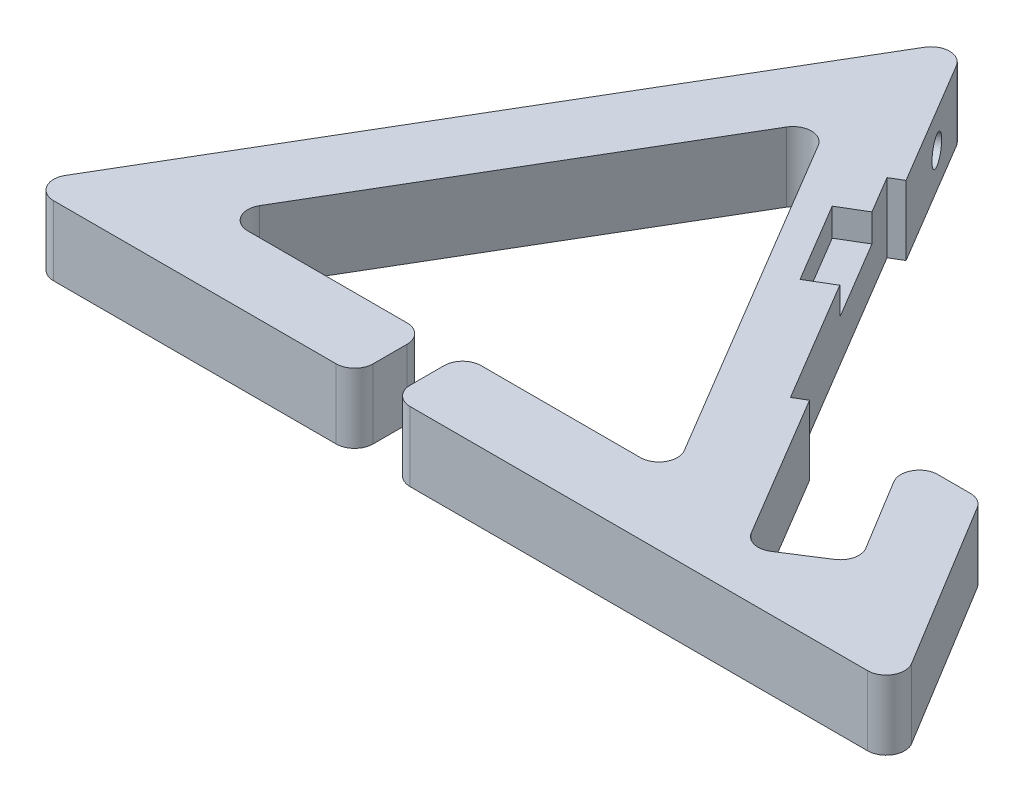
SolidWorks part; units mm, degrees
ref_plane "Front Plane" through (0, 0, 0) normal (0, 0, 1) x (1, 0, 0)
ref_plane "Top Plane" through (0, 0, 0) normal (0, 1, 0) x (1, 0, 0)
ref_plane "Right Plane" through (0, 0, 0) normal (1, 0, 0) x (0, 0, -1)
sketch "Sketch1" plane through (0, 0, 0) normal (0, 1, 0) x (1, 0, 0)
  line L0 (-46.2925, 32.1196) -> (-39.6941, 28.2314) construction
  line L1 (-13.4081, 32.1196) -> (-20.2717, 28.7214) construction
  line L2 (-29.9282, 41.0273) -> (-29.8161, 3.242) construction
  line L3 (-29.9282, 55.9506) -> (-29.9282, 41.0273) construction
  line L4 (0.6, -4.4167) -> (-25.8161, -4.4167)
  line L5 (-31.8161, 1.242) -> (-31.8161, -2.4167)
  line L6 (-52.7385, 6.2574) -> (-31.6513, 42.0427)
  line L7 (-28.2098, 42.0507) -> (-6.8983, 6.2654)
  line L8 (0.6, -4.4167) -> (23.5851, -4.4167)
  line L9 (25.2933, -1.3767) -> (14.2522, 16.7579)
  line L11 (-66.0455, -1.4014) -> (-31.6513, 56.966)
  line L12 (-28.2098, 56.974) -> (4.4186, 2.1858)
  line L13 (-27.8161, 1.242) -> (-27.8161, -2.4167)
  line L14 (-51.0154, 3.242) -> (-33.8161, 3.242)
  line L15 (-25.8161, 3.242) -> (-8.6167, 3.242)
  line L16 (-33.8161, -4.4167) -> (-64.3224, -4.4167)
  line L25 (7.2167, 1.5256) -> (11.4076, 4.2136)
  line L26 (12.0361, 6.9372) -> (7.3233, 14.6777)
  line L27 (9.0316, 17.7178) -> (12.5439, 17.7178)
  arc A0 (23.5851, -4.4167) -> (25.2933, -1.3767) centre (23.5851, -2.4167) ccw
  arc A1 (-8.6167, 3.242) -> (-6.8983, 6.2654) centre (-8.6167, 5.242) ccw
  arc A2 (-25.8161, 3.242) -> (-27.8161, 1.242) centre (-25.8161, 1.242) ccw
  arc A3 (-31.6513, 42.0427) -> (-28.2098, 42.0507) centre (-29.9282, 41.0273) cw
  arc A4 (-51.0154, 3.242) -> (-52.7385, 6.2574) centre (-51.0154, 5.242) cw
  arc A5 (-25.8161, -4.4167) -> (-27.8161, -2.4167) centre (-25.8161, -2.4167) cw
  arc A6 (-31.8161, -2.4167) -> (-33.8161, -4.4167) centre (-33.8161, -2.4167) cw
  arc A7 (-64.3224, -4.4167) -> (-66.0455, -1.4014) centre (-64.3224, -2.4167) cw
  arc A8 (-31.6513, 56.966) -> (-28.2098, 56.974) centre (-29.9282, 55.9506) cw
  arc A9 (12.5439, 17.7178) -> (14.2522, 16.7579) centre (12.5439, 15.7178) cw
  arc A10 (7.3233, 14.6777) -> (9.0316, 17.7178) centre (9.0316, 15.7178) cw
  arc A11 (12.0361, 6.9372) -> (11.4076, 4.2136) centre (10.3278, 5.8971) cw
  arc A12 (4.4186, 2.1858) -> (7.2167, 1.5256) centre (6.137, 3.2091) ccw
  arc A13 (-31.8161, 1.242) -> (-33.8161, 3.242) centre (-33.8161, 1.242) ccw
  point P9 (5.4724, 17.7178)
  point P13 (13.0521, 5.2684)
  point P18 (5.4765, 0.4094)
  point P38 (-27.8161, 3.242)
  dimension "D3" = 2
  dimension "D1" = 2
  dimension "D2" = 4
extrude "Boss-Extrude1" add sketch "Sketch1" along normal blind 7.5
sketch "Sketch2" plane through (4.2227, 0, -2.5148) normal (0.8592, 0, -0.5117) x (-0.5117, 0, -0.8592)
  line L0 (57.2818, 3.75) -> (0.2818, 3.75) construction
  line L3 (63.3851, 3.75) -> (57.2818, 3.75) construction
  line L4 (63.3851, 7.5) -> (63.3851, 0) construction
  circle A0 centre (57.2818, 3.75) radius 1.5
  dimension "D2" = 3
  dimension "D1" = 57
extrude "Cut-Extrude1" cut sketch "Sketch2" against normal blind 9
ref_plane "Plane1" through (3.3635, 0, -2.0031) normal (0.8592, 0, -0.5117) x (-0.5117, 0, -0.8592)
sketch "Sketch5" plane through (3.3635, 0, -2.0031) normal (0.8592, 0, -0.5117) x (-0.5117, 0, -0.8592)
  line L0 (57.2818, 5.35) -> (57.2818, 2.15) construction
  arc A0 (59.352, 5.2072) -> (59.4061, 2.15) centre (57.5442, 3.6461) cw construction
  arc A1 (59.6878, 1.9237) -> (59.6254, 5.4434) centre (57.5442, 3.6461) ccw
  arc A2 (59.1245, 2.3763) -> (59.0785, 4.9711) centre (57.5442, 3.6461) ccw
  arc A3 (59.1245, 2.3763) -> (59.6878, 1.9237) centre (59.4061, 2.15) ccw
  arc A4 (59.6254, 5.4434) -> (59.0785, 4.9711) centre (59.352, 5.2072) ccw
  arc A5 (55.2115, 5.2072) -> (55.1574, 2.15) centre (57.0193, 3.6461) ccw construction
  arc A6 (54.8757, 1.9237) -> (54.9381, 5.4434) centre (57.0193, 3.6461) cw
  arc A7 (55.439, 2.3763) -> (55.485, 4.9711) centre (57.0193, 3.6461) cw
  arc A8 (55.439, 2.3763) -> (54.8757, 1.9237) centre (55.1574, 2.15) cw
  arc A9 (54.9381, 5.4434) -> (55.485, 4.9711) centre (55.2115, 5.2072) cw
  point P3 (59.9324, 3.6884)
  point P13 (54.6311, 3.6884)
extrude "Cut-Extrude4" cut sketch "Sketch5" against normal blind 7
sketch "Sketch6" plane through (11.8624, 0, -7.2224) normal (-0.8541, 0, 0.52) x (0.52, 0, 0.8541)
  line L0 (-1.0214, 3.75) -> (-8.7284, 3.75) construction
  line L1 (-8.7284, 7.5) -> (-8.7284, 0) construction
  circle A0 centre (-1.0214, 3.75) radius 1.25
  point P5 (-8.7284, 3.75)
  dimension "D1" = 2.5
extrude "Boss-Extrude2" add sketch "Sketch6" along normal blind 2
fillet "Fillet1" radius 1 1 edges at (10.273, 3.75, -5.9871)
sketch "Sketch7" plane through (0, 7.5, 0) normal (0, -1, 0) x (1, 0, 0)
  line L0 (-17.7973, -39.4897) -> (-29.9373, -59.8746) construction
  line L1 (-31.6513, -56.966) -> (-29.9373, -59.8746) construction
  line L2 (-17.7973, -39.4897) -> (-21.7752, -37.1206)
  line L3 (-21.7752, -37.1206) -> (-16.6585, -28.5288)
  line L4 (-16.6585, -28.5288) -> (-12.6805, -30.8979)
  line L5 (-12.6805, -30.8979) -> (-17.7973, -39.4897)
extrude "Cut-Extrude5" cut sketch "Sketch7" along normal blind 3
sketch "Sketch8" plane through (4.2227, 0, -2.5148) normal (0.8592, 0, -0.5117) x (-0.5117, 0, -0.8592)
  line L0 (17.7182, 7.5) -> (17.7182, 0)
  line L1 (17.7182, 0) -> (47.7182, 0)
  line L2 (47.7182, 0) -> (47.7182, 7.5)
  line L3 (47.7182, 7.5) -> (17.7182, 7.5)
  line L4 (-0.3829, 7.5) -> (33.0351, 7.5) construction
  line L5 (-2.3818, 7.5) -> (-2.3818, 0) construction
  line L6 (-0.3829, 0) -> (63.3851, 0) construction
  dimension "D1" = 30
  dimension "D3" = 20.1
extrude "Cut-Extrude6" cut sketch "Sketch8" against normal blind 1.5
